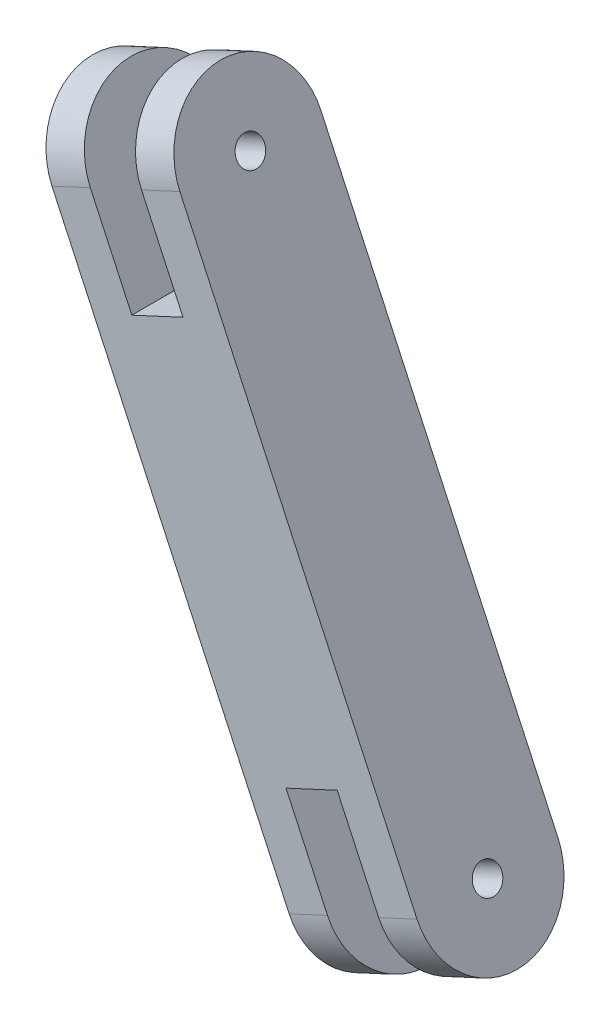
SolidWorks part; units mm, degrees
ref_plane "Plan de face" through (0, 0, 0) normal (0, 0, 1) x (1, 0, 0)
ref_plane "Plan de dessus" through (0, 0, 0) normal (0, 1, 0) x (1, 0, 0)
ref_plane "Plan de droite" through (0, 0, 0) normal (1, 0, 0) x (0, 0, -1)
sketch "Esquisse1" plane through (0, 0, 0) normal (0, 0, 1) x (1, 0, 0)
  line L0 (-101.8731, 116.8692) -> (-80.8448, 71.5061)
  line L1 (-101.8731, 116.8692) -> (-92.8005, 121.0748)
  line L2 (-80.8448, 71.5061) -> (-71.7722, 75.7118)
  line L3 (-92.8005, 121.0748) -> (-71.7722, 75.7118)
  line L4 (-101.8731, 116.8692) -> (-71.7722, 75.7118) construction
  line L5 (-80.8448, 71.5061) -> (-92.8005, 121.0748) construction
  line L6 (-78.4113, 78.1452) -> (-95.234, 114.4357) construction
  line L7 (-99.1514, 118.1309) -> (-94.1046, 107.2437)
  line L8 (-94.1046, 107.2437) -> (-90.4755, 108.926)
  line L9 (-90.4755, 108.926) -> (-95.5223, 119.8131)
  line L10 (-95.5223, 119.8131) -> (-92.8005, 121.0748)
  line L11 (-99.1514, 118.1309) -> (-101.8731, 116.8692)
  line L12 (-80.8448, 71.5061) -> (-78.123, 72.7678)
  line L17 (-78.123, 72.7678) -> (-83.1698, 83.6549)
  line L18 (-83.1698, 83.6549) -> (-79.5408, 85.3372)
  line L23 (-79.5408, 85.3372) -> (-74.494, 74.4501)
  point P1 (-86.8227, 96.2905)
  point P8 (-86.8227, 96.2905)
  dimension "D1" = 50
  dimension "D2" = 10
  dimension "D3" = 3
  dimension "D4" = 3
  dimension "D5" = 12
  dimension "D6" = 3
  dimension "D7" = 3
  dimension "D8" = 12
extrude "Boss.-Extru.1" add sketch "Esquisse1" along normal blind 10 contours L9 L8 L7 L1 L0 L2 L3
sketch "Esquisse2" plane through (-39.2611, -18.1997, 0) normal (-0.9073, -0.4206, 0) x (0, 0, 1)
  line L0 (0, 143.8754) -> (10, 143.8754) construction
  line L1 (0, 148.8754) -> (0, 98.8754) construction
  line L2 (10, 148.8754) -> (10, 98.8754) construction
  line L3 (10, 143.8754) -> (10, 103.8754) construction
  line L4 (10, 103.8754) -> (0, 103.8754) construction
  line L5 (10, 148.8754) -> (0, 148.8754) construction
  line L6 (10, 98.8754) -> (0, 98.8754) construction
  line L7 (5, 143.8754) -> (5, 103.8754) construction
  line L8 (10, 143.8754) -> (10, 103.8754)
  line L9 (0, 143.8754) -> (0, 103.8754)
  line L10 (0, 148.8754) -> (10, 148.8754)
  line L11 (10, 148.8754) -> (10, 98.8754)
  line L12 (10, 98.8754) -> (0, 98.8754)
  line L13 (0, 98.8754) -> (0, 148.8754)
  arc A0 (10, 143.8754) -> (0, 143.8754) centre (5, 143.8754) ccw
  arc A1 (0, 103.8754) -> (10, 103.8754) centre (5, 103.8754) ccw
  circle A2 centre (5, 143.8754) radius 1
  circle A3 centre (5, 103.8754) radius 1
  point P14 (5, 123.8754)
  line M8 (0, 148.8754) -> (0, 98.8754)
  line M9 (0, 98.8754) -> (10, 98.8754)
  line M10 (10, 98.8754) -> (10, 148.8754)
  line M11 (10, 148.8754) -> (0, 148.8754)
  dimension "D4" = 2
  dimension "D5" = 2
  dimension "D1" = 5
  dimension "D2" = 5
  dimension "D3" = 5
extrude "Enlèv. mat.-Extru.1" cut sketch "Esquisse2" against normal blind 20 contours A0 L10 M8 | A0 M10 M11 | A2 | A1 L12 M10 | A1 M8 M9 | A3
